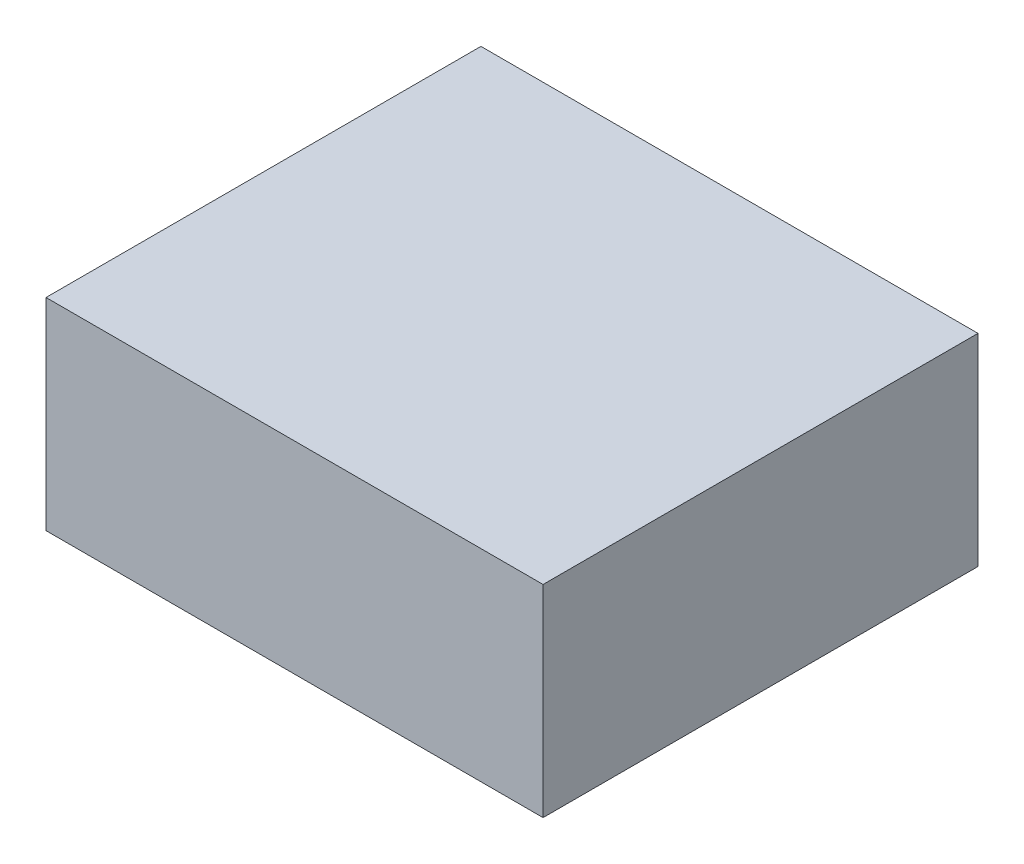
SolidWorks part; units mm, degrees
ref_plane "Front Plane" through (0, 0, 0) normal (0, 0, 1) x (1, 0, 0)
ref_plane "Top Plane" through (0, 0, 0) normal (0, 1, 0) x (1, 0, 0)
ref_plane "Right Plane" through (0, 0, 0) normal (1, 0, 0) x (0, 0, -1)
sketch "Sketch1" plane through (0, 0, 0) normal (0, 0, 1) x (1, 0, 0)
  line L1 (-80, -32.5) -> (80, -32.5)
  line L2 (-80, -32.5) -> (-80, 32.5)
  line L3 (-80, 32.5) -> (80, 32.5)
  line L4 (80, -32.5) -> (80, 32.5)
  line L5 (-80, -32.5) -> (80, 32.5) construction
  line L6 (-80, 32.5) -> (80, -32.5) construction
  point P0 (0, 0)
  dimension "D1" = 160
  dimension "D2" = 65
extrude "Boss-Extrude1" add sketch "Sketch1" along normal mid plane 140
equation "\"D1@Sketch1\"=160mm"
equation "\"D2@Sketch1\"=65mm"
equation "\"D1@Boss-Extrude1\"=140mm"
